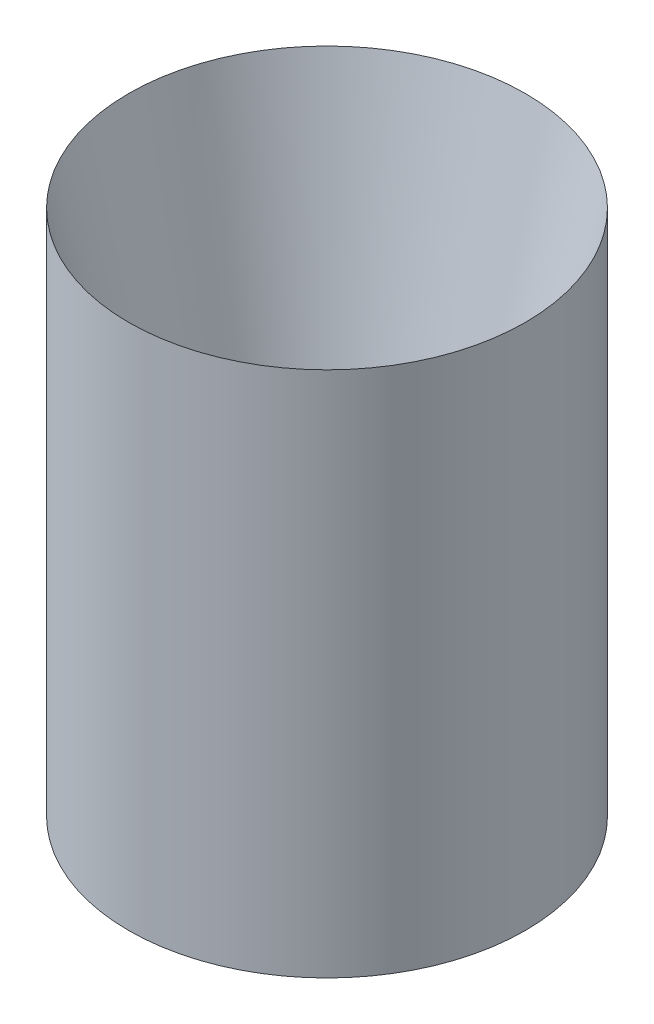
SolidWorks part; units mm, degrees
ref_plane "Front Plane" through (0, 0, 0) normal (1, 0, 0) x (0, 1, 0)
ref_plane "Top Plane" through (0, 0, 0) normal (0, 0, 1) x (0, 1, 0)
ref_plane "Right Plane" through (0, 0, 0) normal (0, 1, 0) x (-1, 0, 0)
sketch "Sketch1" plane through (0, 0, 0) normal (0, 0, 1) x (0, 1, 0)
  line L0 (0, 22.225) -> (0, 53.848)
  line L1 (0, 53.848) -> (143.002, 53.848)
  line L2 (143.002, 53.848) -> (0, 22.225)
  line L3 (0, 0) -> (143.002, 0) construction
  point P0 (0, 22.225)
  dimension "D1" = 22.225
  dimension "D2" = 53.848
  dimension "D3" = 143.002
revolve "Revolve1" add sketch "Sketch1" angle 360 about L3
